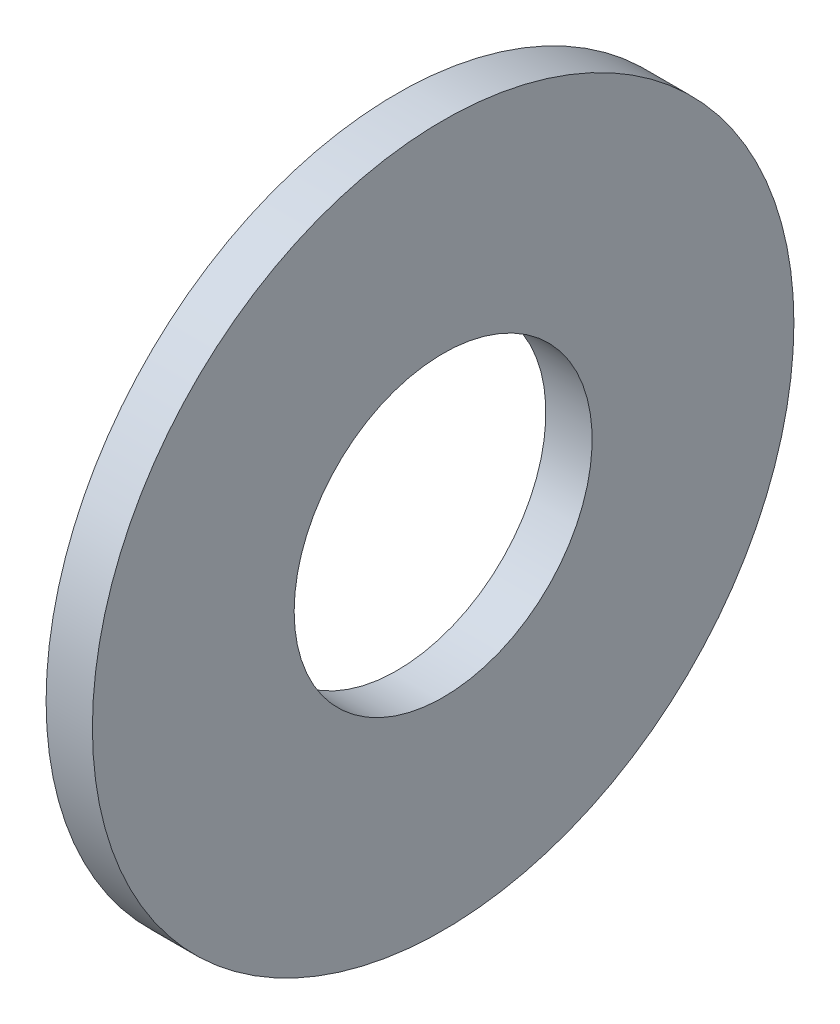
SolidWorks part; units mm, degrees
ref_plane "Plane1" through (0, 0, 0) normal (0, 0, 1) x (1, 0, 0)
ref_plane "Plane2" through (0, 0, 0) normal (0, 1, 0) x (1, 0, 0)
ref_plane "Plane3" through (0, 0, 0) normal (1, 0, 0) x (0, 0, -1)
sketch "Sketch1" plane through (0, 0, 0) normal (0, 0, 1) x (1, 0, 0)
  line L0 (-34.925, 0) -> (9.525, 0) construction
  line L1 (0, 13.4874) -> (0, 31.75)
  line L2 (0, 31.75) -> (-4.191, 31.75)
  line L3 (-4.191, 31.75) -> (-4.191, 13.4874)
  line L4 (-4.191, 13.4874) -> (0, 13.4874)
  dimension "Thickness" = 4.191
  dimension "Inside_dia" = 26.9748
  dimension "Outside_dia" = 63.5
revolve "Base-Revolve" add sketch "Sketch1" angle 360 about L0
